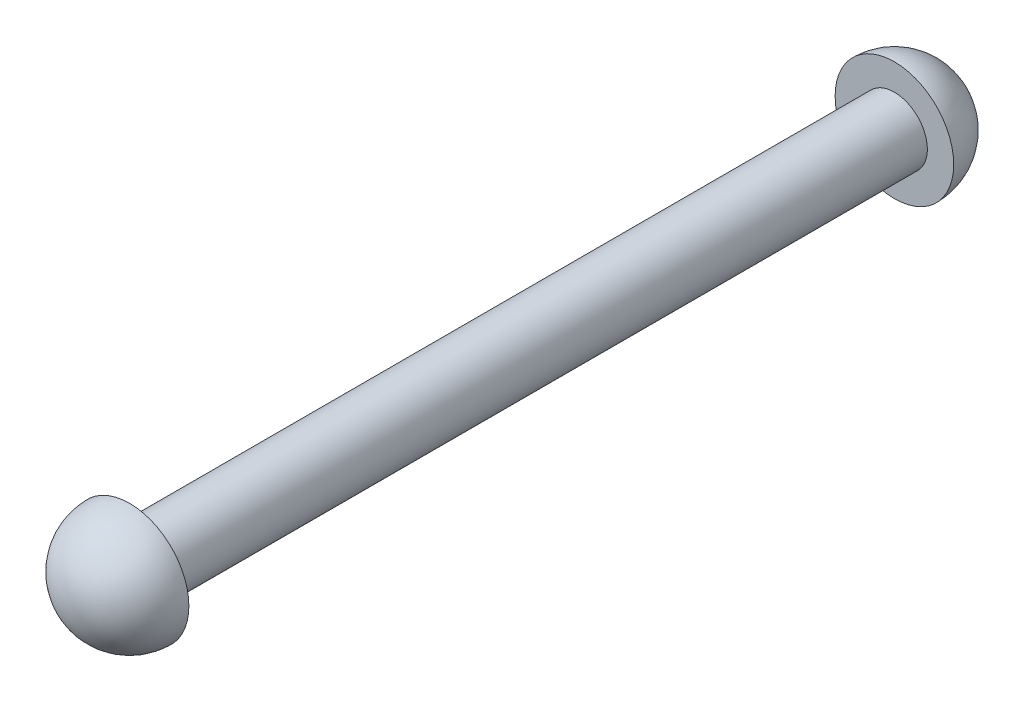
SolidWorks part; units mm, degrees
material "AISI 1020"
ref_plane "Front Plane" through (0, 0, 0) normal (0, 0, 1) x (1, 0, 0)
ref_plane "Top Plane" through (0, 0, 0) normal (0, 1, 0) x (1, 0, 0)
ref_plane "Right Plane" through (0, 0, 0) normal (1, 0, 0) x (0, 0, -1)
sketch "Sketch2" plane through (0, 0, 0) normal (1, 0, 0) x (0, 0, -1)
  line L0 (-36.83, -5.7098) -> (-36.83, -3.175)
  line L1 (-36.83, -3.175) -> (36.83, -3.175)
  line L2 (-36.83, -3.175) -> (-36.83, 3.175)
  line L3 (-36.83, 3.175) -> (36.83, 3.175)
  line L4 (36.83, -3.175) -> (36.83, 3.175)
  line L5 (-42.5398, 0) -> (42.5398, 0) construction
  line L7 (-36.83, 3.175) -> (-36.83, 5.7098)
  line L8 (36.83, 3.175) -> (36.83, 5.7098)
  line L9 (36.83, -5.7098) -> (36.83, -3.175)
  arc A0 (-36.83, 5.7098) -> (-36.83, -5.7098) centre (-36.83, 0) ccw
  arc A1 (36.83, -5.7098) -> (36.83, 5.7098) centre (36.83, 0) ccw
  point P0 (0, 0)
revolve "Revolve1" add sketch "Sketch2" angle 360 about L5
